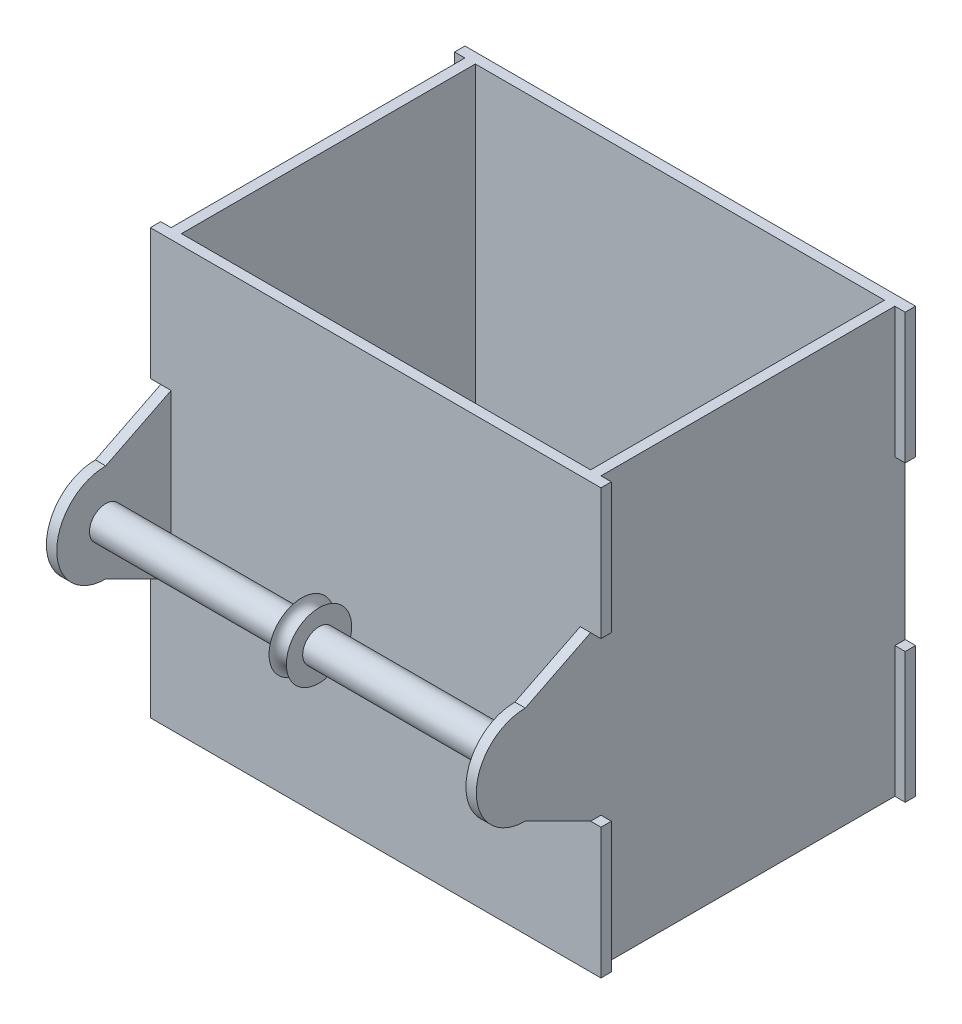
SolidWorks part; units mm, degrees
ref_plane "Front Plane" through (0, 0, 0) normal (0, 0, 1) x (1, 0, 0)
ref_plane "Top Plane" through (0, 0, 0) normal (0, 1, 0) x (1, 0, 0)
ref_plane "Right Plane" through (0, 0, 0) normal (1, 0, 0) x (0, 0, -1)
sketch "Sketch2" plane through (0, 0, 0) normal (0, 0, 1) x (1, 0, 0)
  line L0 (0, 50) -> (-3.175, 50)
  line L1 (131.65, 50) -> (0, 50) construction
  line L2 (131.65, 50) -> (131.65, 0)
  line L3 (131.65, 0) -> (0, 0) construction
  line L4 (0, 50) -> (0, 0)
  line L5 (-3.175, 50) -> (-3.175, 90)
  line L6 (-3.175, 90) -> (134.825, 90)
  line L7 (134.825, 90) -> (134.825, 50)
  line L8 (134.825, 50) -> (131.65, 50)
  line L9 (0, 0) -> (-3.175, 0)
  line L10 (-3.175, 0) -> (-3.175, -40)
  line L11 (-3.175, -40) -> (134.825, -40)
  line L12 (134.825, -40) -> (134.825, 0)
  line L13 (134.825, 0) -> (131.65, 0)
  dimension "D1" = 50
  dimension "D2" = 131.65
  dimension "D3" = 3.175
  dimension "D4" = 40
extrude "Boss-Extrude1" add sketch "Sketch2" along normal blind 3.175
sketch "Sketch3" plane through (0, 0, 3.175) normal (0, 0, 1) x (1, 0, 0)
  line L0 (-3.175, -40) -> (134.825, -40) construction
  line L1 (0, -40) -> (3.175, -40)
  line L2 (0, -40) -> (0, 90)
  line L3 (0, 90) -> (3.175, 90)
  line L4 (3.175, -40) -> (3.175, 90)
  line L5 (134.825, 90) -> (-3.175, 90) construction
  line L6 (131.65, 0) -> (131.65, 50) construction
  line L7 (131.65, -40) -> (128.475, -40)
  line L8 (131.65, -40) -> (131.65, 90)
  line L9 (131.65, 90) -> (128.475, 90)
  line L10 (128.475, -40) -> (128.475, 90)
  dimension "D1" = 3.175
  dimension "D2" = 3.175
extrude "Boss-Extrude2" add sketch "Sketch3" along normal blind 90
sketch "Sketch4" plane through (0, 0, 93.175) normal (0, 0, 1) x (1, 0, 0)
  line L0 (131.65, 50) -> (134.825, 50)
  line L1 (134.825, 50) -> (134.825, 90)
  line L2 (134.825, 90) -> (-3.175, 90)
  line L3 (-3.175, 90) -> (-3.175, 50)
  line L4 (-3.175, 50) -> (-1.5875, 50)
  line L5 (-3.175, 50) -> (0, 50) construction
  line L6 (-1.5875, 50) -> (0, 50)
  line L7 (0, 50) -> (0, 0)
  line L8 (0, 0) -> (-3.175, 0)
  line L9 (-3.175, 0) -> (-3.175, -40)
  line L10 (-3.175, -40) -> (134.825, -40)
  line L11 (134.825, -40) -> (134.825, 0)
  line L12 (134.825, 0) -> (131.65, 0)
  line L13 (131.65, -40) -> (131.65, 90) construction
  line L14 (131.65, 0) -> (131.65, 50)
extrude "Boss-Extrude3" add sketch "Sketch4" along normal blind 3.175
sketch "Sketch5" plane through (0, 0, 0) normal (-1, 0, 0) x (0, 0, 1)
  line L0 (96.35, 50) -> (96.35, 0)
  line L2 (116.35, 40) -> (96.35, 50)
  line L3 (116.35, 10) -> (96.35, 0)
  arc A0 (116.35, 10) -> (116.35, 40) centre (116.35, 25) ccw
extrude "Boss-Extrude4" add sketch "Sketch5" against normal blind 3.175
sketch "Sketch6" plane through (131.65, 0, 0) normal (1, 0, 0) x (0, 0, -1)
  line L0 (-96.35, 25) -> (-116.35, 25) construction
  line L1 (-96.35, 0) -> (-96.35, 50) construction
  line L2 (-96.35, 0) -> (-116.35, 10)
  line L3 (-116.35, 40) -> (-96.35, 50)
  line L4 (-96.35, 0) -> (-96.35, 50)
  arc A0 (-116.35, 40) -> (-116.35, 10) centre (-116.35, 25) ccw
extrude "Boss-Extrude5" add sketch "Sketch6" against normal blind 3.175
sketch "Sketch7" plane through (131.65, 0, 0) normal (1, 0, 0) x (0, 0, -1)
  circle A0 centre (-116.35, 25) radius 5
extrude "Boss-Extrude6" add sketch "Sketch7" against normal up to surface (128.475 mm away) up to face at (3.175, 25, 110.1)
ref_plane "Plane1" through (68.475, 0, 0) normal (-1, 0, 0) x (0, 0, 1)
sketch "Sketch8" plane through (68.475, 0, 0) normal (-1, 0, 0) x (0, 0, 1)
  line L0 (116.35, 40) -> (116.35, 10) construction
  circle A0 centre (116.35, 25) radius 10
extrude "Boss-Extrude7" add sketch "Sketch8" along normal blind 5.3
ref_plane "Plane2" through (0, 25, 0) normal (0, 1, 0) x (1, 0, 0)
sketch "Sketch10" plane through (0, 25, 0) normal (0, 1, 0) x (1, 0, 0)
  line L0 (68.475, -106.35) -> (63.175, -106.35) construction
  line L1 (63.175, -116.35) -> (43.5801, -116.35) construction
  line L2 (63.175, -111.35) -> (63.175, -121.35) construction
  circle A0 centre (65.825, -106.35) radius 2.65
revolve "Cut-Revolve1" cut sketch "Sketch10" angle 360 about L1
